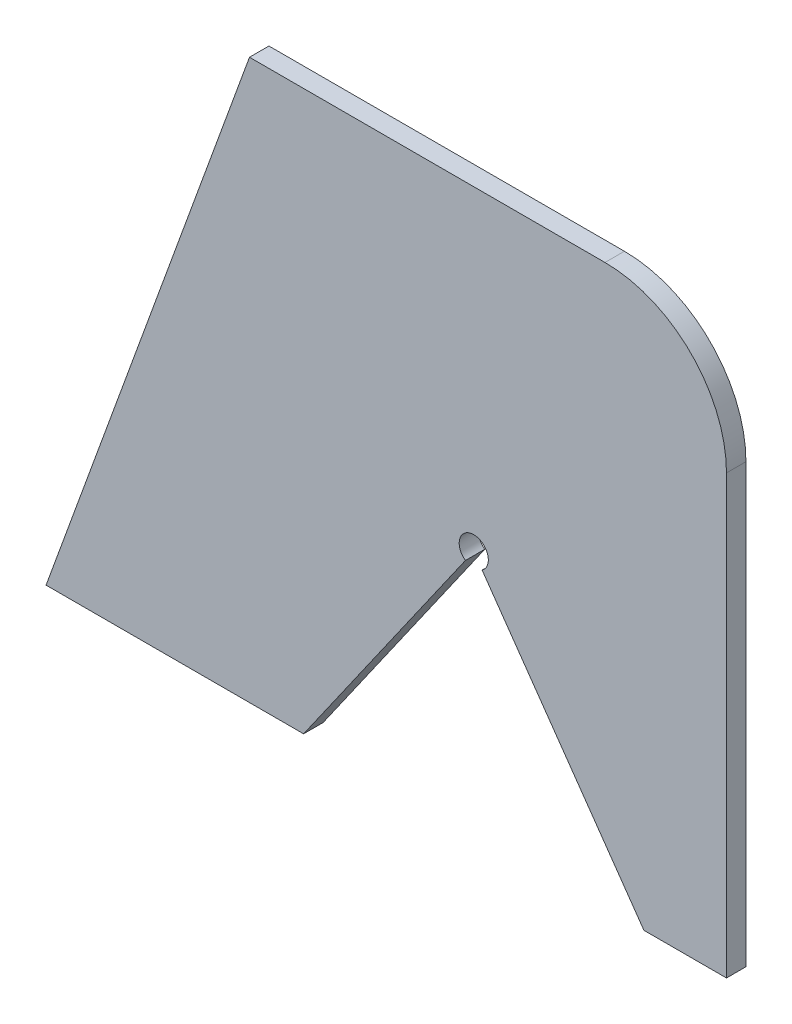
SolidWorks part; units mm, degrees
ref_plane "Ebene vorne" through (0, 0, 0) normal (0, 0, 1) x (1, 0, 0)
ref_plane "Ebene oben" through (0, 0, 0) normal (0, 1, 0) x (1, 0, 0)
ref_plane "Ebene rechts" through (0, 0, 0) normal (1, 0, 0) x (0, 0, -1)
sketch "Skizze1" plane through (0, 0, 0) normal (0, 0, 1) x (1, 0, 0)
  line L0 (0, 0) -> (52.9896, 0)
  line L1 (52.9896, 0) -> (86.2793, 47.5425)
  line L2 (89.7207, 47.5425) -> (123.0104, 0)
  line L3 (123.0104, 0) -> (140, 0)
  line L4 (140, 0) -> (140, 90)
  line L5 (115, 115) -> (41.8566, 115)
  line L6 (41.8566, 115) -> (0, 0)
  line L7 (88, 50) -> (88, -12.2863) construction
  arc A0 (89.7207, 47.5425) -> (86.2793, 47.5425) centre (88, 50) ccw
  arc A1 (115, 115) -> (140, 90) centre (115, 90) cw
  dimension "D7" = 6
  dimension "D9" = 25
  dimension "D1" = 140
  dimension "D2" = 115
  dimension "D3" = 70
  dimension "D4" = 52
  dimension "D5" = 70
  dimension "D6" = 50
  dimension "D8" = 35
extrude "Aufsatz-Linear austragen1" add sketch "Skizze1" along normal blind 4
